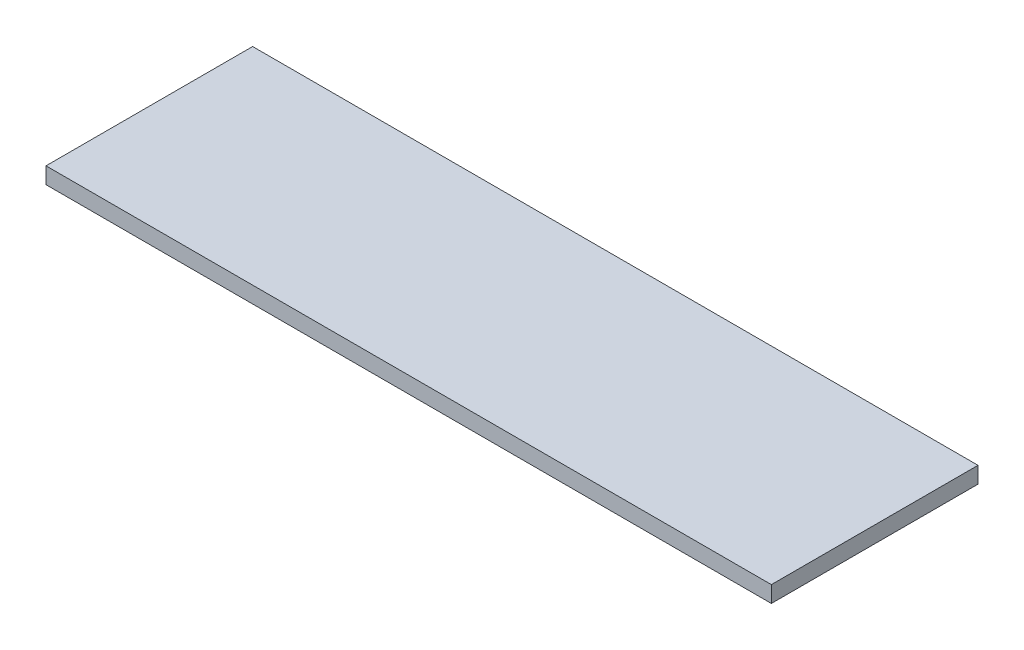
SolidWorks part; units mm, degrees
ref_plane "Front Plane" through (0, 0, 0) normal (0, 0, 1) x (1, 0, 0)
ref_plane "Top Plane" through (0, 0, 0) normal (0, 1, 0) x (1, 0, 0)
ref_plane "Right Plane" through (0, 0, 0) normal (1, 0, 0) x (0, 0, -1)
sketch "Sketch1" plane through (0, 0, 0) normal (0, 0, 1) x (1, 0, 0)
  line L0 (-15, -18) -> (133, -18) construction
  line L1 (-15, -18) -> (-813.2365, -18)
  line L2 (-15, -18) -> (-15, 0)
  line L3 (-15, 0) -> (-813.2365, 0)
  line L4 (-813.2365, -18) -> (-813.2365, 0)
  dimension "D1" = 18
extrude "Boss-Extrude1" add sketch "Sketch1" along normal up to body (209.4 mm away) and the other way blind 18 separate body
equation "\"osbthickness\"=18"
equation "\"D1@Sketch1\"=\"osbthickness\""
